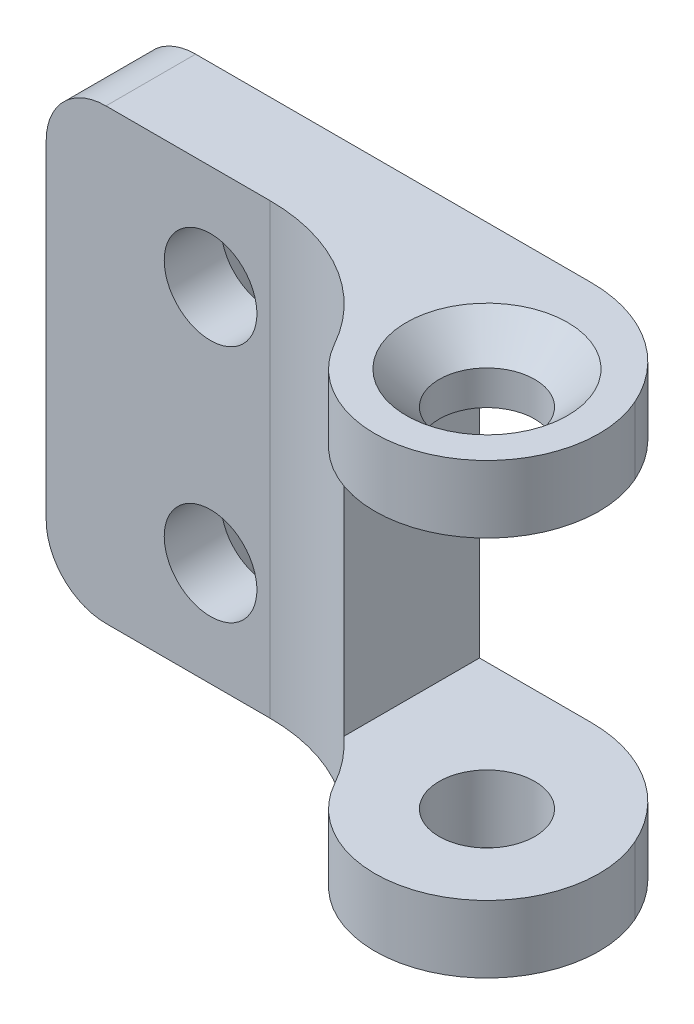
SolidWorks part; units mm, degrees
material "1060 Сплав"
ref_plane "Спереди" through (0, 0, 0) normal (0, 0, 1) x (1, 0, 0)
ref_plane "Сверху" through (0, 0, 0) normal (0, 1, 0) x (1, 0, 0)
ref_plane "Справа" through (0, 0, 0) normal (1, 0, 0) x (0, 0, -1)
sketch "Эскиз1" plane through (0, 0, 0) normal (0, 1, 0) x (1, 0, 0)
  line L0 (-32, 8.5) -> (-1.5384, 8.5)
  line L1 (-17.0294, 2.5) -> (-32, 2.5)
  line L2 (-32, 2.5) -> (-32, 8.5)
  arc A0 (-6.5498, -3.6538) -> (6.8542, 3.0445) centre (0, 0) ccw
  circle A1 centre (0, 0) radius 3.2
  arc A2 (-17.0294, 2.5) -> (-6.5498, -3.6538) centre (-17.0294, -9.5) cw
  arc A3 (-1.5384, 8.5) -> (6.8542, 3.0445) centre (-1.5384, -0.6833) cw
  dimension "D2" = 6.4
  dimension "D6" = 32
  dimension "D3" = 8.5
  dimension "D4" = 6
extrude "Бобышка-Вытянуть1" add sketch "Эскиз1" along normal blind 30
fillet "Скругление1" radius 4 2 edges at (-32, 0, -5.5) (-32, 30, -5.5)
sketch "Эскиз2" plane through (0, 0, -8.5) normal (0, 0, -1) x (-1, 0, 0)
  line L0 (1.5384, 0) -> (28, 0) construction
  line L1 (32, 26) -> (32, 4) construction
  circle A0 centre (21, 23) radius 3.1
  circle A1 centre (21, 7) radius 3.1
  dimension "D1" = 16
  dimension "D4" = 6.2
  dimension "D2" = 7
  dimension "D3" = 11
extrude "Вырез-Вытянуть1" cut sketch "Эскиз2" against normal through all
sketch "Эскиз3" plane through (0, 0, -8.5) normal (0, 0, -1) x (-1, 0, 0)
  line L0 (9, 25.5) -> (9, 4.5)
  line L1 (9, 4.5) -> (-13.4629, 4.5)
  line L2 (-13.4629, 4.5) -> (-13.4629, 25.5)
  line L3 (-13.4629, 25.5) -> (9, 25.5)
  line L4 (1.5384, 30) -> (-6.8542, 30) construction
  line L5 (32, 26) -> (32, 4) construction
  dimension "D1" = 4.5
  dimension "D2" = 4.5
  dimension "D3" = 23
extrude "Вырез-Вытянуть2" cut sketch "Эскиз3" against normal through all
chamfer "Фаска1" distance 2.2 angle 45 1 edges at (0, 30, 3.2)
chamfer "Фаска2" distance 2.2 angle 45 1 edges at (-24.1, 23, -8.5)
chamfer "Фаска3" distance 2.2 angle 45 1 edges at (-24.1, 7, -8.5)
